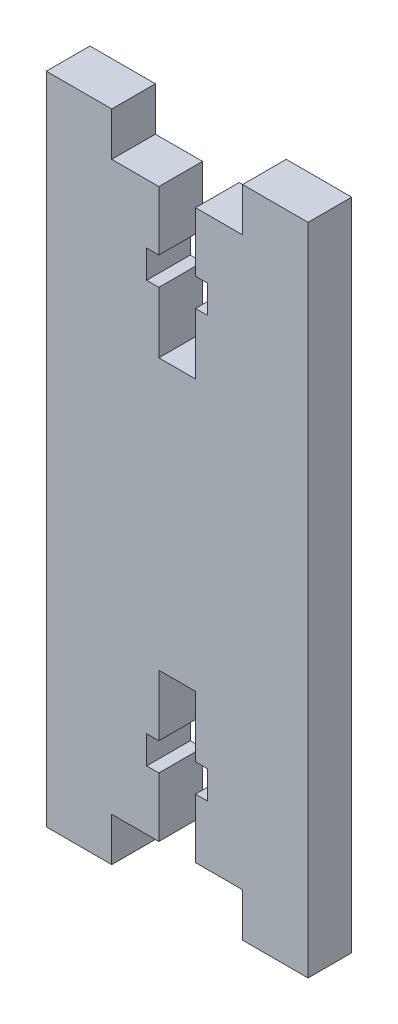
SolidWorks part; units mm, degrees
ref_plane "Front Plane" through (0, 0, 0) normal (0, 0, 1) x (1, 0, 0)
ref_plane "Top Plane" through (0, 0, 0) normal (0, 1, 0) x (1, 0, 0)
ref_plane "Right Plane" through (0, 0, 0) normal (1, 0, 0) x (0, 0, -1)
sketch "Sketch1" plane through (0, 0, 0) normal (0, 0, 1) x (1, 0, 0)
  line L0 (-15, 65) -> (-15, 53.5434) construction
  line L1 (0, 0) -> (-30, 0)
  line L2 (0, 0) -> (0, 65)
  line L3 (0, 65) -> (-30, 65)
  line L4 (-30, 0) -> (-30, 65)
  line L13 (-30, 65) -> (-22.5, 65)
  line L14 (-30, 65) -> (-30, 70)
  line L15 (-30, 70) -> (-22.5, 70)
  line L16 (-22.5, 65) -> (-22.5, 70)
  line L17 (-17.1, 65) -> (-17.1, 58.2)
  line L18 (-17.1, 55) -> (-18.5, 55)
  line L19 (-18.5, 55) -> (-18.5, 58.2)
  line L20 (-18.5, 58.2) -> (-17.1, 58.2)
  line L21 (-17.1, 55) -> (-17.1, 48)
  line L22 (-17.1, 48) -> (-12.9, 48)
  line L23 (-17.1, 65) -> (-12.9, 65)
  line L24 (-12.9, 55) -> (-12.9, 48)
  line L25 (-11.5, 58.2) -> (-12.9, 58.2)
  line L26 (-11.5, 55) -> (-11.5, 58.2)
  line L27 (-12.9, 55) -> (-11.5, 55)
  line L28 (-12.9, 65) -> (-12.9, 58.2)
  line L29 (-7.5, 65) -> (-7.5, 70)
  line L30 (0, 70) -> (-7.5, 70)
  line L31 (0, 65) -> (0, 70)
  line L32 (0, 65) -> (-7.5, 65)
  line L33 (-30, 32.5) -> (-15, 32.5) construction
  line L34 (-15, 0) -> (-15, 11.4566) construction
  line L35 (0, 0) -> (-7.5, 0)
  line L36 (0, 0) -> (0, -5)
  line L37 (0, -5) -> (-7.5, -5)
  line L38 (-7.5, 0) -> (-7.5, -5)
  line L39 (-12.9, 0) -> (-12.9, 6.8)
  line L40 (-12.9, 10) -> (-11.5, 10)
  line L41 (-11.5, 10) -> (-11.5, 6.8)
  line L42 (-11.5, 6.8) -> (-12.9, 6.8)
  line L43 (-12.9, 10) -> (-12.9, 17)
  line L44 (-17.1, 0) -> (-12.9, 0)
  line L45 (-17.1, 17) -> (-12.9, 17)
  line L46 (-17.1, 10) -> (-17.1, 17)
  line L47 (-18.5, 6.8) -> (-17.1, 6.8)
  line L48 (-18.5, 10) -> (-18.5, 6.8)
  line L49 (-17.1, 10) -> (-18.5, 10)
  line L50 (-17.1, 0) -> (-17.1, 6.8)
  line L51 (-22.5, 0) -> (-22.5, -5)
  line L52 (-30, -5) -> (-22.5, -5)
  line L53 (-30, 0) -> (-30, -5)
  line L54 (-30, 0) -> (-22.5, 0)
  point P19 (-15, 48)
  point P48 (-15, 17)
  dimension "D1" = 5
  dimension "D2" = 65
  dimension "D3" = 30
  dimension "D4" = 7.5
  dimension "D5" = 2.1
  dimension "D6" = 3.5
  dimension "D7" = 17
  dimension "D8" = 6.8
  dimension "D9" = 3.2
extrude "Boss-Extrude1" add sketch "Sketch1" along normal blind 5 contours L1 L50 L47 L48 L49 L46 L45 L43 L40 L41 L42 L39 L2 L3 L28 L25 L26 L27 L24 L22 L21 L18 L19 L20 L17 L4 | L3 L31 L30 L29 | L3 L16 L15 L14 | L1 L53 L52 L51 | L1 L38 L37 L36
